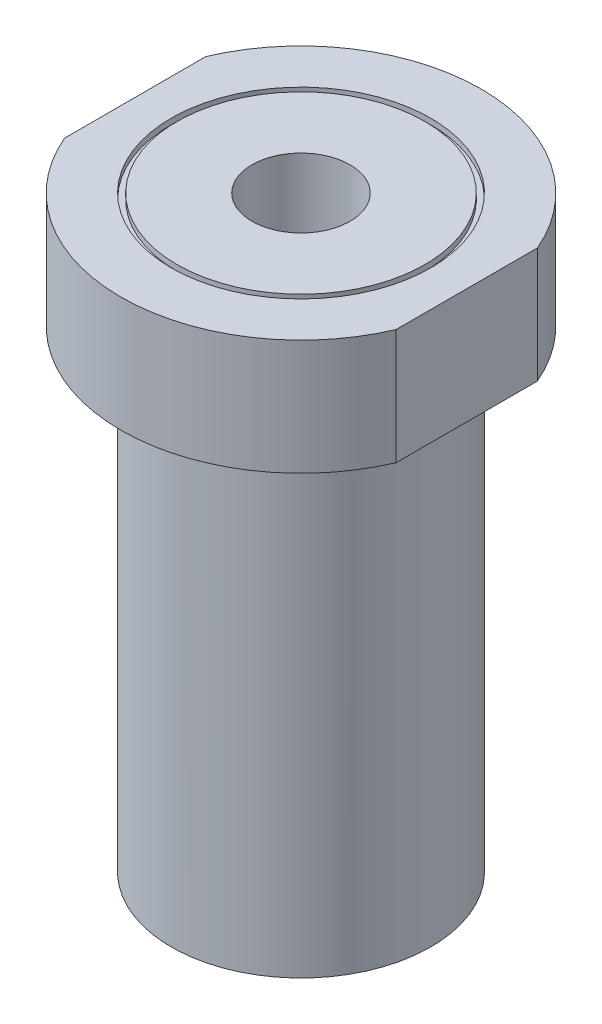
SolidWorks part; units mm, degrees
ref_plane "前视基准面" through (0, 0, 0) normal (0, 0, 1) x (1, 0, 0)
ref_plane "上视基准面" through (0, 0, 0) normal (0, 1, 0) x (1, 0, 0)
ref_plane "右视基准面" through (0, 0, 0) normal (1, 0, 0) x (0, 0, -1)
other "Configuration Table"
sketch "草图1" plane through (0, 0, 0) normal (1, 0, 0) x (0, 0, -1)
  line L0 (0, 0) -> (0, 7.7334) construction
  line L1 (0, 0) -> (-3.65, 0) construction
  line L2 (-3.65, 0) -> (-4.5, 0)
  line L3 (-4.5, 0) -> (-4.5, 16.4)
  line L4 (-4.5, 16.4) -> (-6.25, 16.4)
  line L5 (-6.25, 16.4) -> (-6.25, 20.4)
  line L6 (-6.25, 20.4) -> (-1.7, 20.4)
  line L7 (-1.7, 20.4) -> (-1.7, 15.4)
  line L8 (-1.7, 15.4) -> (-3.65, 15.4)
  line L9 (-3.65, 15.4) -> (-3.65, 0)
  point P11 (-4.075, 0)
  dimension "D1" = 4.5
  dimension "D2" = 3.65
  dimension "D3" = 6.25
  dimension "D4" = 20.4
  dimension "D5" = 4
  dimension "D6" = 5
  dimension "D7" = 1.7
revolve "旋转1" add sketch "草图1" angle 360 about L0
chamfer "倒角1" distance 0.5 angle 45 1 edges at (0, 0, -3.65)
fillet "圆角1" radius 1 1 edges at (0, 16.4, -4.5)
sketch "草图2" plane through (0, 20.4, 0) normal (0, 1, 0) x (1, 0, 0)
  line L0 (-5.75, 2.4495) -> (-5.75, -2.4495)
  line L1 (0, 6.25) -> (0, -6.25) construction
  line L2 (5.75, 2.4495) -> (5.75, -2.4495)
  arc A0 (-5.75, 2.4495) -> (-5.75, -2.4495) centre (0, 0) ccw
  arc A1 (5.75, -2.4495) -> (5.75, 2.4495) centre (0, 0) ccw
  dimension "D2" = 12.5
  dimension "D1" = 11.5
extrude "切除-拉伸1" cut sketch "草图2" against normal up to next
sketch "草图3" plane through (0, 20.4, 0) normal (0, 1, 0) x (1, 0, 0)
  circle A0 centre (0, 0) radius 4.5
  circle A1 centre (0, 0) radius 4.3
  dimension "D1" = 9
  dimension "D2" = 0.2
extrude "切除-拉伸2" cut sketch "草图3" against normal blind 0.2
